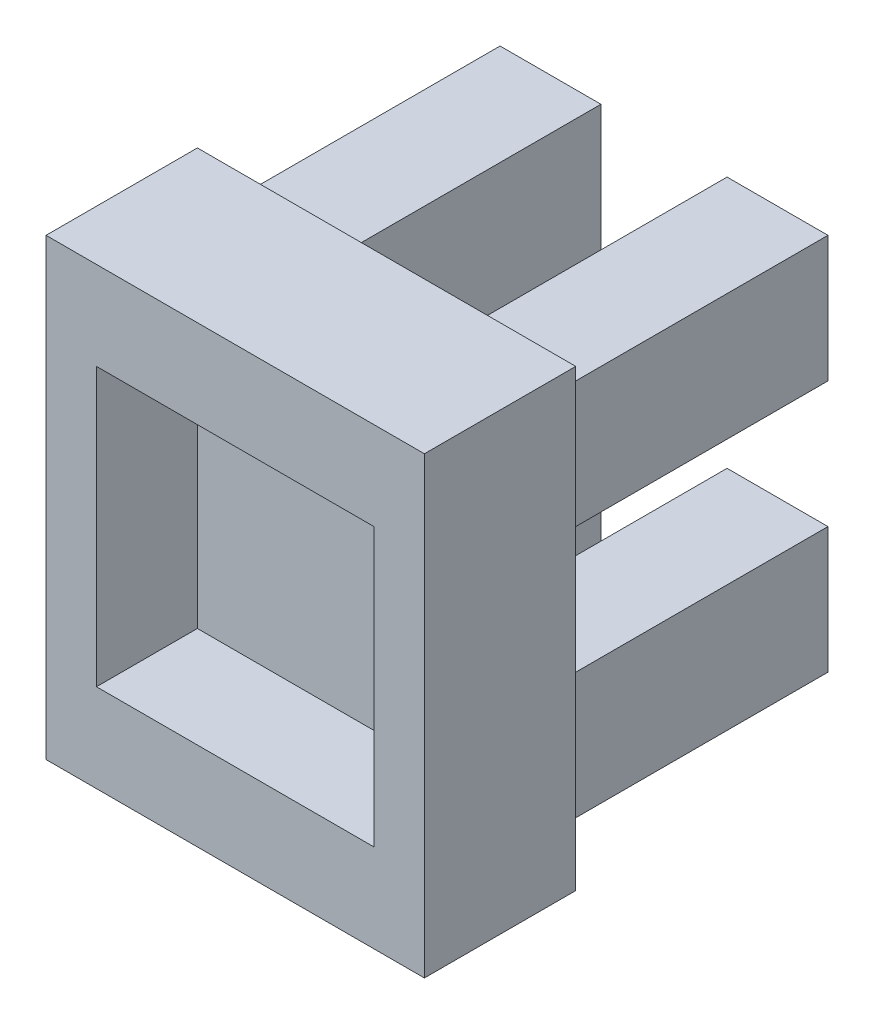
SolidWorks part; units mm, degrees
ref_plane "Front Plane" through (0, 0, 0) normal (0, 0, 1) x (1, 0, 0)
ref_plane "Top Plane" through (0, 0, 0) normal (0, 1, 0) x (1, 0, 0)
ref_plane "Right Plane" through (0, 0, 0) normal (1, 0, 0) x (0, 0, -1)
sketch "Sketch1" plane through (0, 0, 0) normal (0, 0, 1) x (1, 0, 0)
  line L1 (0, 0) -> (15, 0)
  line L2 (0, 0) -> (0, 18)
  line L3 (0, 18) -> (15, 18)
  line L4 (15, 0) -> (15, 18)
  dimension "D1" = 15
  dimension "D2" = 18
extrude "Boss-Extrude1" add sketch "Sketch1" along normal blind 6
sketch "Sketch2" plane through (0, 0, 6) normal (0, 0, 1) x (1, 0, 0)
  line L0 (0, 18) -> (0, 0) construction
  line L1 (2, 14.5) -> (13, 14.5)
  line L2 (2, 14.5) -> (2, 3.5)
  line L3 (2, 3.5) -> (13, 3.5)
  line L4 (13, 14.5) -> (13, 3.5)
  line L5 (15, 0) -> (15, 18) construction
  line L6 (15, 18) -> (0, 18) construction
  line L7 (0, 0) -> (15, 0) construction
  dimension "D1" = 2
  dimension "D2" = 2
  dimension "D3" = 3.5
  dimension "D4" = 3.5
extrude "Cut-Extrude1" cut sketch "Sketch2" against normal blind 4
sketch "Sketch3" plane through (0, 0, 0) normal (0, 0, -1) x (-1, 0, 0)
  line L0 (-15, 18) -> (0, 18) construction
  line L1 (-14, 16.5) -> (-10, 16.5)
  line L2 (-14, 16.5) -> (-14, 11.5)
  line L3 (-14, 11.5) -> (-10, 11.5)
  line L4 (-10, 16.5) -> (-10, 11.5)
  line L5 (-5, 16.5) -> (-1, 16.5)
  line L6 (-5, 16.5) -> (-5, 11.5)
  line L7 (-5, 11.5) -> (-1, 11.5)
  line L8 (-1, 16.5) -> (-1, 11.5)
  line L9 (-14, 6.5) -> (-10, 6.5)
  line L10 (-14, 6.5) -> (-14, 1.5)
  line L11 (-14, 1.5) -> (-10, 1.5)
  line L12 (-10, 6.5) -> (-10, 1.5)
  line L13 (-5, 6.5) -> (-1, 6.5)
  line L14 (-5, 6.5) -> (-5, 1.5)
  line L15 (-5, 1.5) -> (-1, 1.5)
  line L16 (-1, 6.5) -> (-1, 1.5)
  line L17 (0, 0) -> (-15, 0) construction
  line L18 (-15, 0) -> (-15, 18) construction
  dimension "D1" = 5
  dimension "D2" = 5
  dimension "D3" = 4
  dimension "D4" = 4
  dimension "D5" = 4
  dimension "D6" = 4
  dimension "D7" = 5
  dimension "D8" = 5
  dimension "D9" = 5
  dimension "D10" = 5
  dimension "D11" = 1.5
  dimension "D12" = 1.5
  dimension "D13" = 1.5
  dimension "D14" = 1.5
  dimension "D15" = 1
  dimension "D16" = 1
extrude "Boss-Extrude2" add sketch "Sketch3" along normal blind 11
